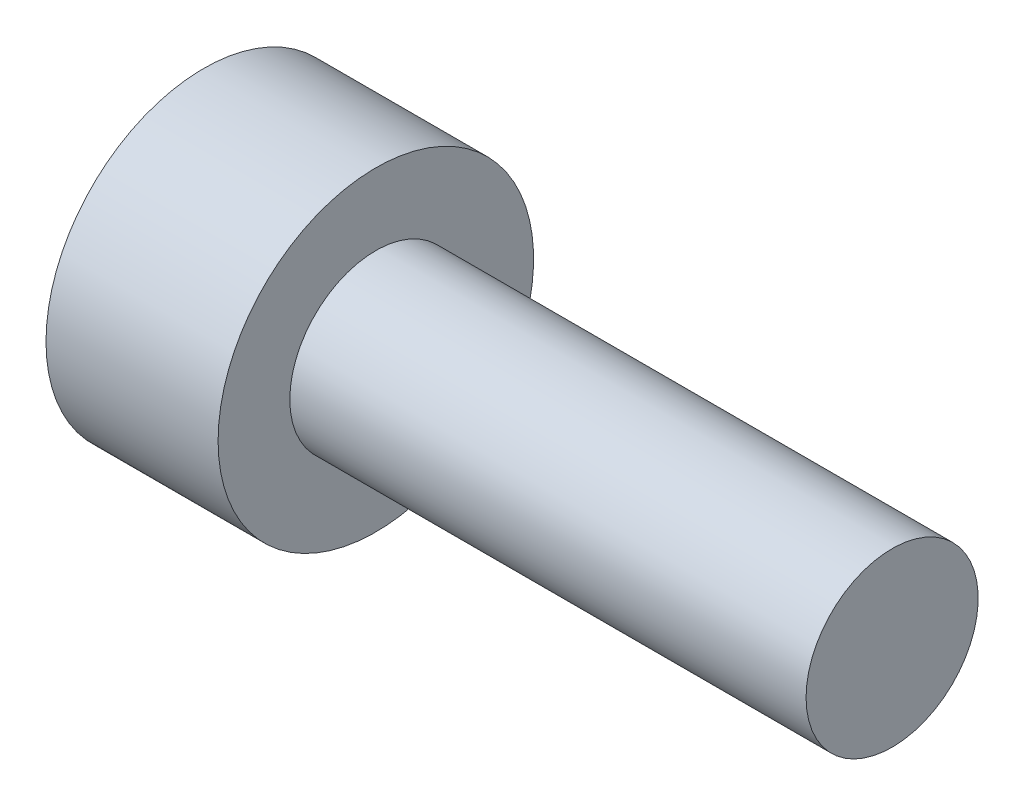
SolidWorks part; units mm, degrees
material "AISI Type 316L stainless steel"
ref_plane "Front Plane" through (0, 0, 0) normal (0, 0, 1) x (1, 0, 0)
ref_plane "Top Plane" through (0, 0, 0) normal (0, 1, 0) x (1, 0, 0)
ref_plane "Right Plane" through (0, 0, 0) normal (1, 0, 0) x (0, 0, -1)
sketch "Axial profile (mm)" plane through (0, 0, 0) normal (0, 0, 1) x (1, 0, 0)
  line L0 (-110, 0) -> (75, 0) construction
  line L1 (-133, 0) -> (-121, 0)
  line L2 (-121, 0) -> (-121, 1.5)
  line L3 (-121, 1.5) -> (-130, 1.5)
  line L4 (-130, 1.5) -> (-130, 2.75)
  line L5 (-130, 2.75) -> (-133, 2.75)
  line L6 (-133, 2.75) -> (-133, 0)
revolve "Full revolution" add sketch "Axial profile (mm)" angle 360 about L0
